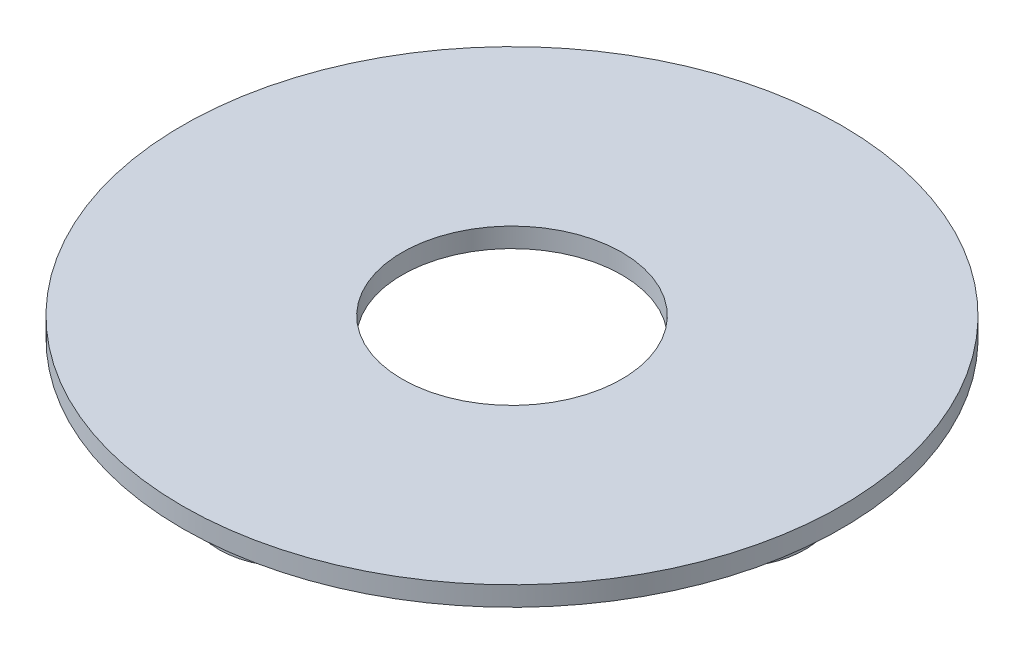
SolidWorks part; units mm, degrees
material "PBT General Purpose"
ref_plane "Front Plane" through (0, 0, 0) normal (0, 0, 1) x (1, 0, 0)
ref_plane "Top Plane" through (0, 0, 0) normal (0, 1, 0) x (1, 0, 0)
ref_plane "Right Plane" through (0, 0, 0) normal (1, 0, 0) x (0, 0, -1)
sketch "Sketch1" plane through (0, 0, 0) normal (0, 1, 0) x (1, 0, 0)
  circle A0 centre (0, 0) radius 4.5
  circle A1 centre (0, 0) radius 13.5
  dimension "D1" = 9
  dimension "D2" = 27
extrude "Boss-Extrude1" add sketch "Sketch1" along normal mid plane 0.8
sketch "Sketch2" plane through (0, 0, 0) normal (0, 1, 0) x (1, 0, 0)
  line L0 (0, -9) -> (0, 9) construction
  line L1 (-9, 0) -> (9, 0) construction
  circle A0 centre (0, 0) radius 9 construction
  circle A1 centre (0, 9) radius 3
  circle A2 centre (9, 0) radius 3
  circle A3 centre (-9, 0) radius 3
  circle A4 centre (0, -9) radius 3
  dimension "D1" = 18
  dimension "D2" = 6
extrude "Boss-Extrude3" add sketch "Sketch2" against normal offset from surface (1.9 mm away) 1.5 up to face at (0, -0.4, 13.5) offset beyond the face yes
